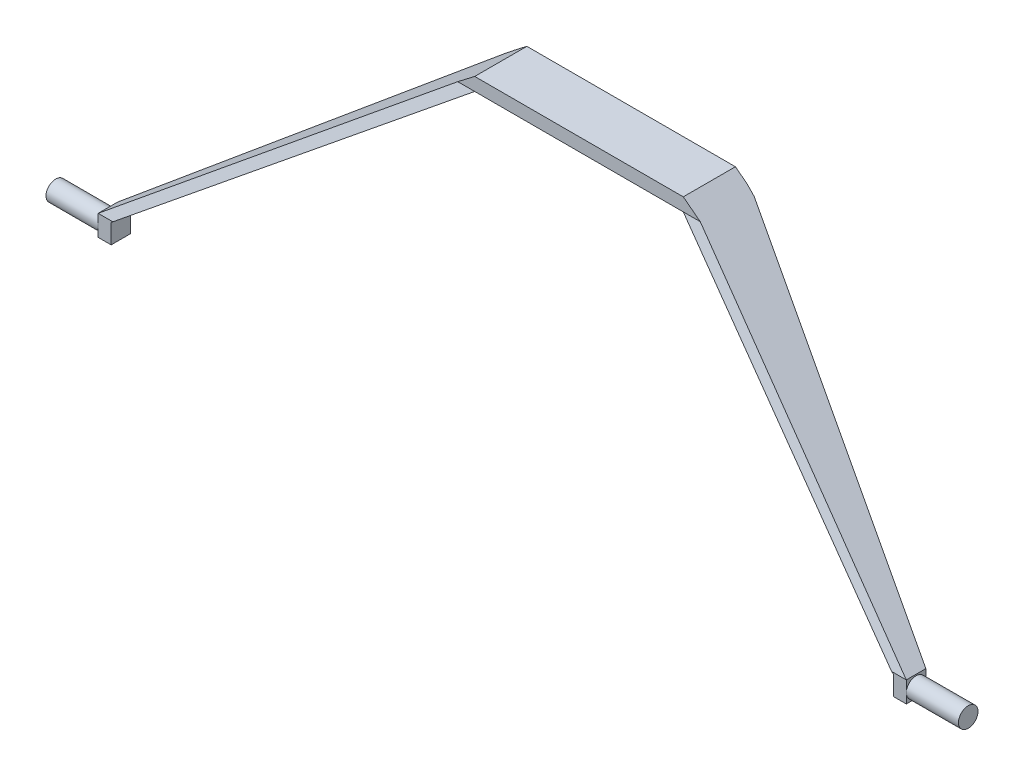
SolidWorks part; units mm, degrees
ref_plane "Front" through (0, 0, 0) normal (0, 0, 1) x (1, 0, 0)
ref_plane "Top" through (0, 0, 0) normal (0, 1, 0) x (1, 0, 0)
ref_plane "Right" through (0, 0, 0) normal (1, 0, 0) x (0, 0, -1)
sketch "Sketch1" plane through (0, 0, 0) normal (0, 0, 1) x (1, 0, 0)
  line L0 (-812.8, -247.65) -> (-812.8, -209.55) construction
  line L1 (-812.8, -228.6) -> (812.8, -228.6) construction
  line L2 (-812.8, -228.6) -> (-812.8, 228.6) construction
  line L3 (-812.8, 228.6) -> (812.8, 228.6) construction
  line L4 (812.8, -228.6) -> (812.8, 228.6) construction
  line L5 (-812.8, -228.6) -> (812.8, 228.6) construction
  line L6 (-812.8, 228.6) -> (812.8, -228.6) construction
  line L7 (-787.4, -228.6) -> (-203.2, -228.6) construction
  line L8 (-787.4, -228.6) -> (-787.4, 228.6) construction
  line L9 (-787.4, 228.6) -> (-203.2, 228.6) construction
  line L10 (-203.2, -228.6) -> (-203.2, 228.6) construction
  line L11 (-787.4717, -247.65) -> (-762.0717, -247.65)
  line L12 (-762.0717, -247.65) -> (-762.0717, -209.55)
  line L13 (-762.0717, -209.55) -> (-203.2, 215.9)
  line L14 (-203.2, 228.6) -> (0, 228.6) construction
  line L15 (-787.4717, -247.65) -> (-787.4, -209.55)
  line L16 (-787.4, -209.55) -> (-787.4, -207.01)
  line L17 (-787.4, -207.01) -> (-203.2, 241.3)
  line L18 (-203.2, 228.6) -> (-203.2, 241.3) construction
  line L19 (-203.2, 228.6) -> (-203.2, 215.9) construction
  line L20 (-203.2, 241.3) -> (203.2, 241.3)
  line L21 (0, 241.3) -> (0, 215.9)
  line L22 (203.2, 215.9) -> (-203.2, 215.9)
  line L23 (0, 228.6) -> (0, -411.3013) construction
  line L24 (787.4, -207.01) -> (203.2, 241.3)
  line L25 (787.4, -209.55) -> (787.4, -207.01)
  line L26 (787.4717, -247.65) -> (787.4, -209.55)
  line L27 (787.4717, -247.65) -> (762.0717, -247.65)
  line L28 (762.0717, -247.65) -> (762.0717, -209.55)
  line L29 (762.0717, -209.55) -> (203.2, 215.9)
  point P0 (0, 0)
  point P13 (-812.8, -228.6)
  dimension "D1" = 1625.6
  dimension "D2" = 457.2
  dimension "D3" = 25.4
  dimension "D4" = 584.2
  dimension "D5" = 38.1
  dimension "D6" = 203.2
  dimension "D7" = 25.4
  dimension "D8" = 2.54
  dimension "D9" = 12.7
  dimension "D10" = 12.7
extrude "Boss-Extrude1" add sketch "Sketch1" against normal blind 101.6 and the other way blind 11.43 contours L22 L21 L20 L17 L16 L15 L11 L12 L13 | L29 L28 L27 L26 L25 L24 L20 L21 L22
sketch "Sketch4" plane through (0, 0, 0) normal (1, 0, 0) x (0, 0, -1)
  line L0 (50.8, -228.6) -> (7.62, -228.6)
  line L1 (101.6, -247.65) -> (101.6, -209.55) construction
  line L2 (7.62, -228.6) -> (-11.43, -228.6)
  dimension "D1" = 43.18
  dimension "D2" = 50.8
  dimension "D3" = 19.05
sketch "Sketch5" plane through (0, 0, 0) normal (1, 0, 0) x (0, 0, -1)
  line L4 (-11.43, -209.55) -> (0, 215.9)
  line L6 (-11.43, -207.01) -> (-11.43, 241.3) construction
  line L7 (-11.43, 215.9) -> (-11.43, -209.55)
  line L9 (-11.43, 215.9) -> (-11.43, 241.3)
  line L12 (0, 241.3) -> (-11.43, 241.3)
  line L14 (0, 241.3) -> (0, 215.9)
  dimension "D1" = 11.43
extrude "Cut-Extrude2" cut sketch "Sketch5" against normal up to next and the other way up to next
sketch "Sketch7" plane through (0, 0, 0) normal (1, 0, 0) x (0, 0, -1)
  line L0 (26.67, -209.55) -> (101.6, 223.9824)
  line L1 (-11.43, -209.55) -> (101.6, -209.55) construction
  line L2 (101.6, -207.01) -> (101.6, 241.3) construction
  line L3 (101.6, 223.9824) -> (101.6, -247.65)
  line L4 (101.6, -247.65) -> (26.67, -247.65)
  line L5 (-11.43, -247.65) -> (101.6, -247.65) construction
  line L6 (26.67, -247.65) -> (26.67, -209.55)
extrude "Cut-Extrude3" cut sketch "Sketch7" against normal up to next and the other way up to next
sketch "Sketch8" plane through (0, 0, 0) normal (0, 0, 1) x (1, 0, 0)
  line L0 (-787.4717, -247.65) -> (-762.0717, -247.65)
  line L1 (-762.0717, -247.65) -> (-762.0717, -209.55)
  line L2 (-762.0717, -209.55) -> (-203.2, 215.9)
  line L3 (-203.2, 215.9) -> (203.2, 215.9)
  line L4 (203.2, 215.9) -> (762.0717, -209.55)
  line L5 (762.0717, -209.55) -> (762.0717, -247.65)
  line L6 (762.0717, -247.65) -> (787.4717, -247.65)
  line L7 (787.4717, -247.65) -> (787.4, -207.01)
  line L8 (787.4, -207.01) -> (203.2, 241.3)
  line L9 (203.2, 241.3) -> (-203.2, 241.3)
  line L10 (-203.2, 241.3) -> (-787.4, -207.01)
  line L11 (-787.4, -207.01) -> (-787.4717, -247.65)
extrude "Boss-Extrude3" add sketch "Sketch8" along normal blind 149.606
sketch "Sketch9" plane through (787.0325, 1.3878, 0) normal (1, 0.0018, 0) x (0, 0, -1)
  line L0 (-149.606, -249.0382) -> (-149.606, -208.3982) construction
  line L1 (-149.606, -249.0382) -> (0, -249.0382) construction
  circle A1 centre (-130.556, -229.9882) radius 19.05
  dimension "D1" = 38.1
  dimension "D2" = 19.05
  dimension "D3" = 19.05
extrude "Boss-Extrude4" add sketch "Sketch9" along normal blind 101.6
mirror "Mirror1" about plane through (0, 0, 0) normal (1, 0, 0) of "Boss-Extrude4"
sketch "Sketch10" plane through (0, 0, 0) normal (1, 0, 0) x (0, 0, -1)
  line L1 (-149.606, -207.01) -> (0, -207.01) construction
  line L2 (-111.506, -207.01) -> (-111.506, -247.65)
  line L3 (-130.556, -247.65) -> (0, -247.65) construction
  line L4 (-111.506, -247.65) -> (101.6, -247.65)
  line L7 (101.6, 215.9) -> (-111.506, -207.01)
  line L8 (101.6, -247.65) -> (101.6, 215.9)
extrude "Cut-Extrude4" cut sketch "Sketch10" against normal up to surface and the other way up to surface up to face at (-499.0611, 14.2587, 11.4838) other way up to face at (499.0611, 14.2587, 11.4838)
sketch "Sketch11" plane through (0, 0, 0) normal (1, 0, 0) x (0, 0, -1)
  line L1 (-149.606, 241.3) -> (101.6, 241.3) construction
  line L2 (0, 241.3) -> (-149.606, 241.3)
  line L3 (-149.606, 241.3) -> (-149.606, -207.01)
  line L4 (0, 241.3) -> (0, 215.9)
  line L5 (0, 215.9) -> (-149.606, -207.01)
  dimension "D1" = 101.6
  dimension "D2" = 25.4
extrude "Cut-Extrude5" cut sketch "Sketch11" against normal up to surface and the other way up to surface up to face at (-408.1274, 84.0405, 18.0074) other way up to face at (408.1274, 84.0405, 18.0074)
